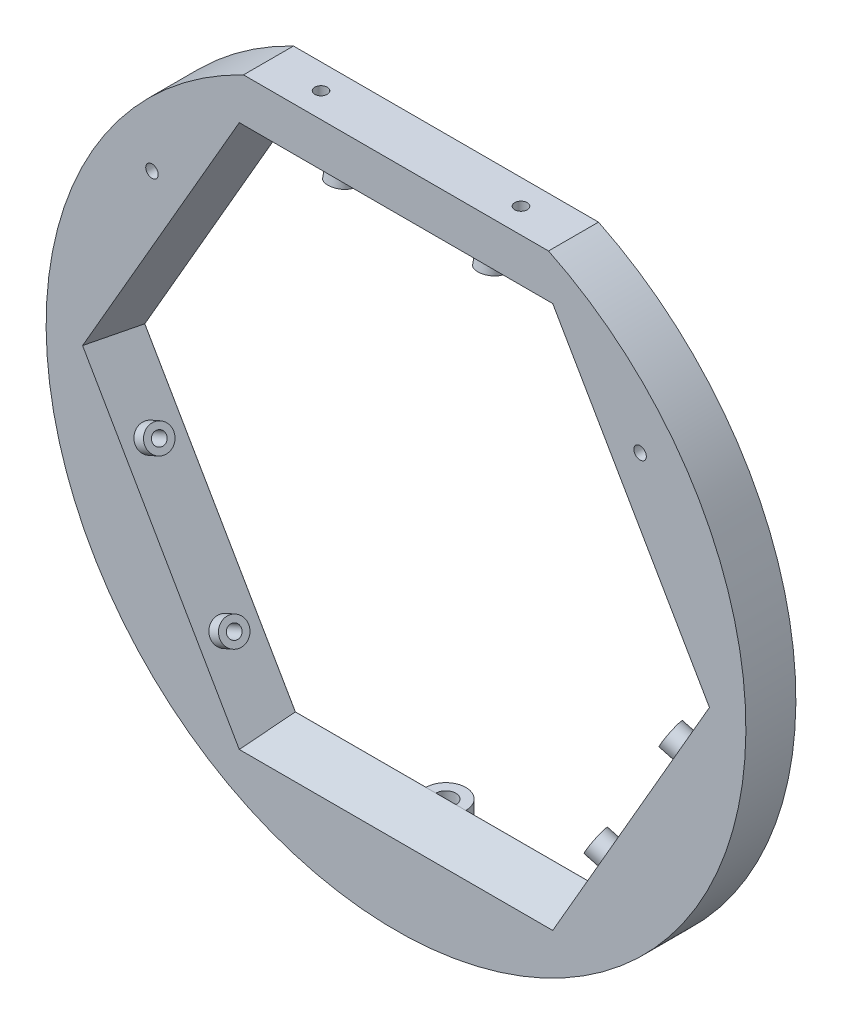
SolidWorks part; units mm, degrees
ref_plane "Plan de face" through (0, 0, 0) normal (0, 0, 1) x (1, 0, 0)
ref_plane "Plan de dessus" through (0, 0, 0) normal (0, 1, 0) x (1, 0, 0)
ref_plane "Plan de droite" through (0, 0, 0) normal (1, 0, 0) x (0, 0, -1)
sketch "Esquisse1" plane through (0, 0, 0) normal (0, 0, 1) x (1, 0, 0)
  line L1 (60.258, 0) -> (30.129, 52.185)
  line L2 (30.129, 52.185) -> (-30.129, 52.185)
  line L3 (-30.129, 52.185) -> (-60.258, 0)
  line L4 (-60.258, 0) -> (-30.129, -52.185)
  line L5 (-30.129, -52.185) -> (30.129, -52.185)
  line L6 (30.129, -52.185) -> (60.258, 0)
  circle A0 centre (0, 0) radius 70
  circle A1 centre (0, 0) radius 52.185 construction
  dimension "D1" = 140
  dimension "D2" = 104.37
extrude "Boss.-Extru.1" add sketch "Esquisse1" along normal blind 10
chamfer "Chanfrein1" distance 2.12 angle 78 6 edges at (-45.1935, 26.0925, 10) (-45.1935, -26.0925, 10) (0, -52.185, 10) (45.1935, -26.0925, 10) (45.1935, 26.0925, 10) (0, 52.185, 10)
sketch "Esquisse2" plane through (-43.2353, -24.9619, -10.6116) normal (0.8471, 0.4891, 0.2079) x (0.1801, 0.104, -0.9781)
  line L0 (-10.8487, 0) -> (-21.0721, 0) construction
  line L1 (-10.8487, 30.1258) -> (-10.8487, -30.1258) construction
  line L2 (-21.0721, -31.353) -> (-21.0721, 31.353) construction
  line L3 (-16.5404, 15) -> (-16.5404, -15) construction
  circle A0 centre (-16.5404, 15) radius 1.25
  circle A1 centre (-16.5404, -15) radius 1.25
  point P12 (-16.5404, 0)
  point P13 (-15.9604, 0)
  dimension "D1" = 2.5
  dimension "D2" = 0.58
  dimension "D3" = 15
extrude "Enlèv. mat.-Extru.1" cut sketch "Esquisse2" against normal blind 8
sketch "Esquisse3" plane through (-43.2353, -24.9619, -10.6116) normal (0.8471, 0.4891, 0.2079) x (0.1801, 0.104, -0.9781)
  circle A0 centre (-16.5404, -15) radius 2.5
  circle A1 centre (-16.5404, 15) radius 2.5
  circle A2 centre (-16.5404, -15) radius 1.25 construction
  circle A3 centre (-16.5404, 15) radius 1.25 construction
  circle A4 centre (-16.5404, -15) radius 1.25
  circle A5 centre (-16.5404, 15) radius 1.25
  dimension "D1" = 5
extrude "Boss.-Extru.2" add sketch "Esquisse3" along normal blind 3
pattern_circular "Répétition circulaire1" count 3 over 360 about axis through (0, 0, 0) along (0, 0, 1) of "Enlèv. mat.-Extru.1", "Boss.-Extru.2"
sketch "Esquisse4" plane through (0, 0, 0) normal (0, 0, -1) x (-1, 0, 0)
  line L0 (30.5123, 63) -> (-30.5123, 63)
  circle A0 centre (0, 0) radius 70 construction
  arc A1 (30.5123, 63) -> (-30.5123, 63) centre (0, 0) ccw
  dimension "D1" = 61.0246
extrude "Enlèv. mat.-Extru.2" cut sketch "Esquisse4" against normal up to next
sketch "Esquisse5" plane through (0, 63, 0) normal (0, 1, 0) x (1, 0, 0)
  line L0 (-30.5123, -10) -> (-30.5123, 0) construction
  line L1 (-20, -5) -> (20, -5) construction
  line L4 (30.5123, -10) -> (-30.5123, -10) construction
  circle A0 centre (-20, -5) radius 1.25
  circle A1 centre (20, -5) radius 1.25
  point P4 (0, -5)
  point P9 (-30.5123, -5)
  point P10 (0, -10)
  dimension "D1" = 2.5
  dimension "D2" = 40
extrude "Enlèv. mat.-Extru.3" cut sketch "Esquisse5" against normal blind 8
sketch "Esquisse6" plane through (0, 0, 0) normal (0, 0, -1) x (-1, 0, 0)
  line L0 (48.824, 37.1794) -> (-48.824, 37.1794) construction
  line L1 (-30.1258, 52.1794) -> (30.1258, 52.1794) construction
  line L2 (56.3524, 41.526) -> (41.2955, 32.8329) construction
  line L3 (30.1258, 52.1794) -> (60.2516, 0) construction
  line L4 (-41.2955, 32.8329) -> (-56.3524, 41.526) construction
  line L5 (-60.2516, 0) -> (-30.1258, 52.1794) construction
  circle A0 centre (48.824, 37.1794) radius 1.25
  circle A1 centre (-48.824, 37.1794) radius 1.25
  arc A2 (-30.5123, 63) -> (30.5123, 63) centre (0, 0) ccw construction
  point P18 (-48.824, 37.1794)
  point P19 (48.824, 37.1794)
  dimension "D2" = 2.5
  dimension "D1" = 15
extrude "Enlèv. mat.-Extru.4" cut sketch "Esquisse6" against normal up to next
ref_plane "Plan1" through (0, -52.185, 0) normal (0, 1, 0) x (1, 0, 0)
sketch "Esquisse7" plane through (0, -52.185, 0) normal (0, 1, 0) x (1, 0, 0)
  line L0 (-30.129, -0.0262) -> (30.129, -0.0262) construction
  line L1 (2, -0.0262) -> (4, -0.0262)
  line L2 (-2, -0.0262) -> (-4, -0.0262)
  arc A0 (4, -0.0262) -> (-4, -0.0262) centre (0, -0.0262) ccw
  arc A1 (2, -0.0262) -> (-2, -0.0262) centre (0, -0.0262) ccw
  dimension "D1" = 2
  dimension "D2" = 2
extrude "Boss.-Extru.3" add sketch "Esquisse7" against normal blind 5
